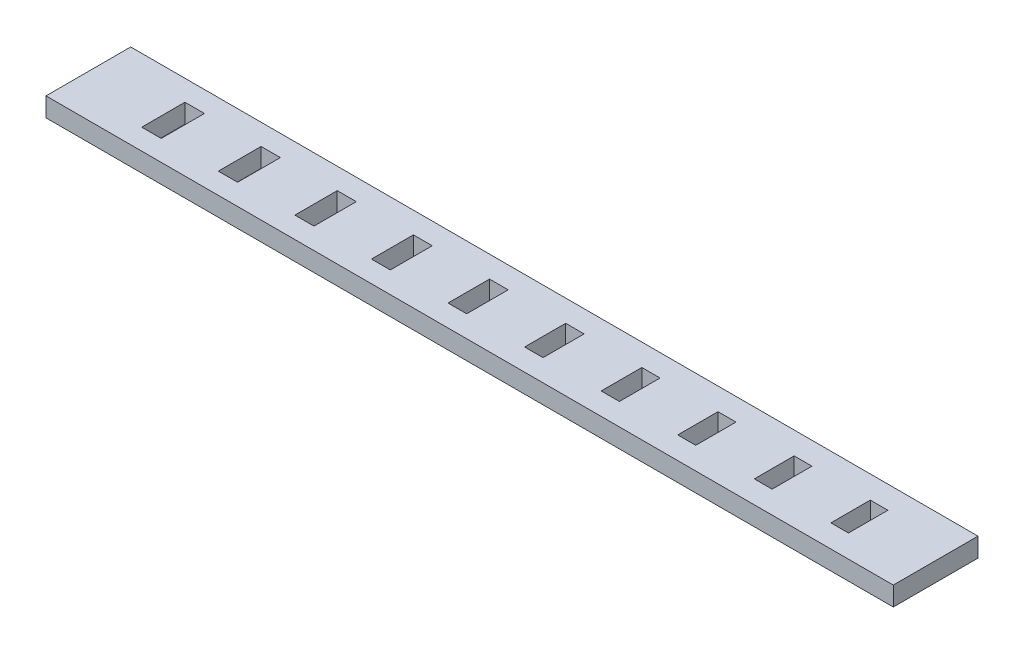
SolidWorks part; units mm, degrees
ref_plane "Front Plane" through (0, 0, 0) normal (0, 0, 1) x (1, 0, 0)
ref_plane "Top Plane" through (0, 0, 0) normal (0, 1, 0) x (1, 0, 0)
ref_plane "Right Plane" through (0, 0, 0) normal (1, 0, 0) x (0, 0, -1)
sketch "Sketch1" plane through (0, 0, 0) normal (0, 1, 0) x (1, 0, 0)
  line L0 (-100, 0) -> (100, 0) construction
  line L1 (-100, -10) -> (100, -10)
  line L2 (-100, -10) -> (-100, 10)
  line L3 (-100, 10) -> (100, 10)
  line L4 (100, -10) -> (100, 10)
  line L5 (-100, -10) -> (100, 10) construction
  line L6 (-100, 10) -> (100, -10) construction
  line L8 (-82.3, -5.1) -> (-77.7, -5.1)
  line L9 (-82.3, -5.1) -> (-82.3, 5.1)
  line L10 (-82.3, 5.1) -> (-77.7, 5.1)
  line L11 (-77.7, -5.1) -> (-77.7, 5.1)
  line L12 (-82.3, -5.1) -> (-77.7, 5.1) construction
  line L13 (-82.3, 5.1) -> (-77.7, -5.1) construction
  line L14 (-64.275, -5.05) -> (-59.725, -5.05)
  line L15 (-64.275, -5.05) -> (-64.275, 5.05)
  line L16 (-64.275, 5.05) -> (-59.725, 5.05)
  line L17 (-59.725, -5.05) -> (-59.725, 5.05)
  line L18 (-64.275, -5.05) -> (-59.725, 5.05) construction
  line L19 (-64.275, 5.05) -> (-59.725, -5.05) construction
  line L20 (-46.25, -5) -> (-41.75, -5)
  line L21 (-46.25, -5) -> (-46.25, 5)
  line L22 (-46.25, 5) -> (-41.75, 5)
  line L23 (-41.75, -5) -> (-41.75, 5)
  line L24 (-46.25, -5) -> (-41.75, 5) construction
  line L25 (-46.25, 5) -> (-41.75, -5) construction
  line L26 (-28.225, -4.95) -> (-23.775, -4.95)
  line L27 (-28.225, -4.95) -> (-28.225, 4.95)
  line L28 (-28.225, 4.95) -> (-23.775, 4.95)
  line L29 (-23.775, -4.95) -> (-23.775, 4.95)
  line L30 (-28.225, -4.95) -> (-23.775, 4.95) construction
  line L31 (-28.225, 4.95) -> (-23.775, -4.95) construction
  line L32 (-5.8, -4.9) -> (-10.2, -4.9)
  line L33 (-5.8, -4.9) -> (-5.8, 4.9)
  line L34 (-5.8, 4.9) -> (-10.2, 4.9)
  line L35 (-10.2, -4.9) -> (-10.2, 4.9)
  line L36 (-5.8, -4.9) -> (-10.2, 4.9) construction
  line L37 (-5.8, 4.9) -> (-10.2, -4.9) construction
  line L38 (12.175, -4.85) -> (7.825, -4.85)
  line L39 (12.175, -4.85) -> (12.175, 4.85)
  line L40 (12.175, 4.85) -> (7.825, 4.85)
  line L41 (7.825, -4.85) -> (7.825, 4.85)
  line L42 (12.175, -4.85) -> (7.825, 4.85) construction
  line L43 (12.175, 4.85) -> (7.825, -4.85) construction
  line L44 (25.85, -4.8) -> (30.15, -4.8)
  line L45 (25.85, -4.8) -> (25.85, 4.8)
  line L46 (25.85, 4.8) -> (30.15, 4.8)
  line L47 (30.15, -4.8) -> (30.15, 4.8)
  line L48 (25.85, -4.8) -> (30.15, 4.8) construction
  line L49 (25.85, 4.8) -> (30.15, -4.8) construction
  line L50 (43.875, -4.75) -> (48.125, -4.75)
  line L51 (43.875, -4.75) -> (43.875, 4.75)
  line L52 (43.875, 4.75) -> (48.125, 4.75)
  line L53 (48.125, -4.75) -> (48.125, 4.75)
  line L54 (43.875, -4.75) -> (48.125, 4.75) construction
  line L55 (43.875, 4.75) -> (48.125, -4.75) construction
  line L56 (61.9, -4.7) -> (66.1, -4.7)
  line L57 (61.9, -4.7) -> (61.9, 4.7)
  line L58 (61.9, 4.7) -> (66.1, 4.7)
  line L59 (66.1, -4.7) -> (66.1, 4.7)
  line L60 (61.9, -4.7) -> (66.1, 4.7) construction
  line L61 (61.9, 4.7) -> (66.1, -4.7) construction
  line L62 (79.925, -4.65) -> (84.075, -4.65)
  line L63 (79.925, -4.65) -> (79.925, 4.65)
  line L64 (79.925, 4.65) -> (84.075, 4.65)
  line L65 (84.075, -4.65) -> (84.075, 4.65)
  line L66 (79.925, -4.65) -> (84.075, 4.65) construction
  line L67 (79.925, 4.65) -> (84.075, -4.65) construction
  point P0 (0, 0)
  point P8 (-80, 0)
  point P13 (-62, 0)
  point P18 (-44, 0)
  point P23 (-26, 0)
  point P28 (-8, 0)
  point P33 (10, 0)
  point P38 (28, 0)
  point P43 (46, 0)
  point P48 (64, 0)
  point P53 (82, 0)
  dimension "D1" = 200
  dimension "D2" = 20
  dimension "D3" = 4.6
  dimension "D4" = 10.2
  dimension "D5" = 4.55
  dimension "D6" = 4.5
  dimension "D7" = 4.45
  dimension "D8" = 4.4
  dimension "D9" = 4.35
  dimension "D10" = 4.3
  dimension "D11" = 4.25
  dimension "D12" = 4.2
  dimension "D13" = 4.15
  dimension "D14" = 10.1
  dimension "D15" = 10
  dimension "D16" = 9.9
  dimension "D17" = 9.8
  dimension "D18" = 9.7
  dimension "D19" = 9.6
  dimension "D20" = 9.5
  dimension "D21" = 9.4
  dimension "D22" = 9.3
  dimension "D23" = 18
  dimension "D24" = 18
  dimension "D25" = 18
  dimension "D26" = 18
  dimension "D27" = 18
  dimension "D28" = 18
  dimension "D29" = 18
  dimension "D30" = 18
  dimension "D31" = 18
  dimension "D32" = 20
extrude "Boss-Extrude1" add sketch "Sketch1" along normal blind 4.5
equation "\"K1\" = - .05"
equation "\"K2\" = - .025"
equation "\"K3\" = - 0"
equation "\"K4\" = .025"
equation "\"K5\" = 0.05"
equation "\"K6\"= .075"
equation "\"K7\"= .1"
equation "\"K8\" = .125"
equation "\"K9\" = .15"
equation "\"K10\" = .175"
equation "\"THICK\" = 4.5"
equation "\"D3@Sketch1\"=\"THICK\"-\"K1\"*2"
equation "\"D4@Sketch1\"=\"TAB\"-\"K1\"*4"
equation "\"D5@Sketch1\"=\"THICK\"-\"K2\"*2"
equation "\"D6@Sketch1\"=\"THICK\"-\"K3\"*2"
equation "\"D7@Sketch1\"=\"THICK\"-\"K4\"*2"
equation "\"D8@Sketch1\"=\"THICK\"-\"K5\"*2"
equation "\"D9@Sketch1\"=\"THICK\"-\"K6\"*2"
equation "\"D10@Sketch1\"=\"THICK\"-\"K7\"*2"
equation "\"D11@Sketch1\"=\"THICK\"-\"K8\"*2"
equation "\"D12@Sketch1\"=\"THICK\"-\"K9\"*2"
equation "\"D13@Sketch1\"=\"THICK\"-\"K10\"*2"
equation "\"D14@Sketch1\"=\"TAB\"-\"K2\"*4"
equation "\"D15@Sketch1\"=\"TAB\"-\"K3\"*4"
equation "\"D16@Sketch1\"=\"TAB\"-\"K4\"*4"
equation "\"D17@Sketch1\"=\"TAB\"-\"K5\"*4"
equation "\"D18@Sketch1\"=\"TAB\"-\"K6\"*4"
equation "\"D19@Sketch1\"=\"TAB\"-\"K7\"*4"
equation "\"D20@Sketch1\" = \"TAB\" - \"K8\" * 4"
equation "\"D21@Sketch1\"=\"TAB\"-\"K9\"*4"
equation "\"D22@Sketch1\"=\"TAB\"-\"K10\"*4"
equation "\"D1@Boss-Extrude1\"=\"THICK\""
equation "\"TAB\"= 10"
